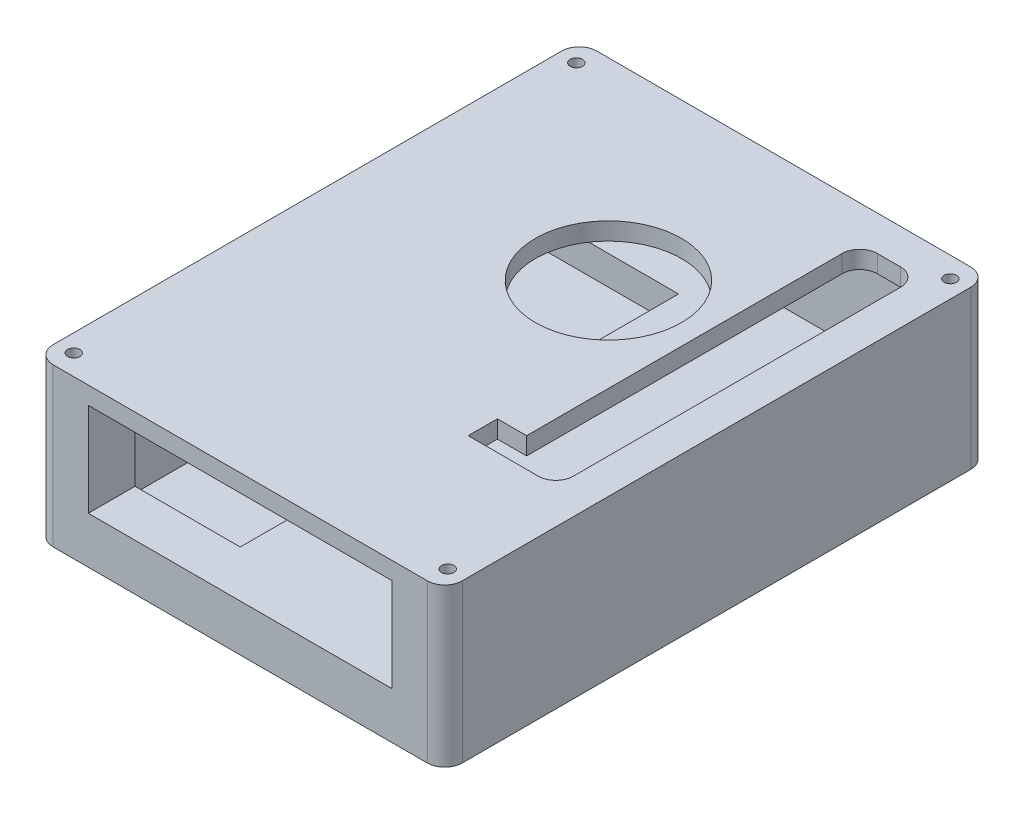
SolidWorks part; units mm, degrees
ref_plane "前视基准面" through (0, 0, 0) normal (0, 0, 1) x (1, 0, 0)
ref_plane "上视基准面" through (0, 0, 0) normal (0, 1, 0) x (1, 0, 0)
ref_plane "右视基准面" through (0, 0, 0) normal (1, 0, 0) x (0, 0, -1)
sketch "草图1" plane through (0, 0, 0) normal (0, 1, 0) x (1, 0, 0)
  line L1 (-32, -46.5) -> (32, -46.5)
  line L2 (-35, -43.5) -> (-35, 43.5)
  line L3 (-32, 46.5) -> (32, 46.5)
  line L4 (35, -43.5) -> (35, 43.5)
  line L5 (-35, -46.5) -> (35, 46.5) construction
  line L6 (-35, 46.5) -> (35, -46.5) construction
  arc A0 (-32, -46.5) -> (-35, -43.5) centre (-32, -43.5) cw
  arc A1 (32, -46.5) -> (35, -43.5) centre (32, -43.5) ccw
  arc A2 (32, 46.5) -> (35, 43.5) centre (32, 43.5) cw
  arc A3 (-35, 43.5) -> (-32, 46.5) centre (-32, 43.5) cw
  point P0 (0, 0)
  dimension "D3" = 3
  dimension "D1" = 93
  dimension "D2" = 70
extrude "凸台-拉伸1" add sketch "草图1" along normal blind 27
sketch "草图2" plane through (-35, 0, 0) normal (-1, 0, 0) x (0, 0, 1)
  line L0 (-43.5, 0) -> (43.5, 0) construction
  line L1 (-36.5, 17) -> (18.5, 17)
  line L2 (-36.5, 17) -> (-36.5, 3)
  line L3 (-36.5, 3) -> (18.5, 3)
  line L4 (18.5, 17) -> (18.5, 3)
  line L5 (-36.5, 17) -> (18.5, 3) construction
  line L6 (-36.5, 3) -> (18.5, 17) construction
  line L7 (-46.5, 27) -> (-46.5, 0) construction
  point P0 (-9, 10)
  point P7 (-5.2874, 10)
  dimension "D1" = 55
  dimension "D2" = 14
  dimension "D3" = 3
  dimension "D4" = 10
extrude "切除-拉伸1" cut sketch "草图2" against normal blind 27
sketch "草图3" plane through (0, 0, 46.5) normal (0, 0, 1) x (1, 0, 0)
  line L0 (0, 0) -> (0, 16) construction
  line L1 (-26, 24) -> (26, 24)
  line L2 (-26, 24) -> (-26, 8)
  line L3 (-26, 8) -> (26, 8)
  line L4 (26, 24) -> (26, 8)
  line L5 (-26, 24) -> (26, 8) construction
  line L6 (-26, 8) -> (26, 24) construction
  line L7 (-32, 0) -> (32, 0) construction
  point P0 (0, 16)
  dimension "D1" = 52
  dimension "D2" = 16
  dimension "D3" = 8
extrude "切除-拉伸2" cut sketch "草图3" against normal blind 90
sketch "草图4" plane through (0, 27, 0) normal (0, 1, 0) x (1, 0, 0)
  line L0 (32, 46.5) -> (-32, 46.5) construction
  line L1 (26, 40.5) -> (22, 40.5)
  line L2 (29, 37.5) -> (29, -18.5)
  line L3 (26, -21.5) -> (19, -21.5)
  line L4 (19, 37.5) -> (19, -16.5)
  line L5 (35, -43.5) -> (35, 43.5) construction
  line L7 (19, -21.5) -> (14, -21.5)
  line L9 (19, -16.5) -> (14, -16.5)
  line L10 (14, -21.5) -> (14, -16.5)
  arc A0 (29, -18.5) -> (26, -21.5) centre (26, -18.5) cw
  arc A1 (22, 40.5) -> (19, 37.5) centre (22, 37.5) ccw
  arc A2 (26, 40.5) -> (29, 37.5) centre (26, 37.5) cw
  circle A3 centre (3, 13.5) radius 12.5
  point P10 (29, -21.5)
  point P13 (19, 40.5)
  point P16 (29, 40.5)
  dimension "D5" = 3
  dimension "D8" = 25
  dimension "D1" = 10
  dimension "D2" = 62
  dimension "D3" = 6
  dimension "D4" = 6
  dimension "D6" = 5
  dimension "D7" = 5
  dimension "D9" = 32
  dimension "D10" = 33
extrude "切除-拉伸3" cut sketch "草图4" against normal up to surface (19 mm away)
sketch "草图5" plane through (0, 0, 18.5) normal (0, 0, -1) x (-1, 0, 0)
  line L0 (26, 17) -> (30, 17)
  line L1 (26, 17) -> (35, 17) construction
  line L2 (30, 17) -> (30, 3)
  line L3 (8, 3) -> (35, 3) construction
  line L4 (30, 3) -> (8, 3)
  line L5 (8, 3) -> (8, 8)
  line L6 (8, 8) -> (26, 8)
  line L7 (26, 8) -> (26, 17)
  line L8 (35, 3) -> (35, 17) construction
  dimension "D1" = 5
extrude "切除-拉伸4" cut sketch "草图5" against normal blind 20
sketch "草图6" plane through (0, 27, 0) normal (0, 1, 0) x (1, 0, 0)
  line L0 (32, 43) -> (-32, 43) construction
  line L1 (-32, 43) -> (-32, -43) construction
  line L2 (-32, -43) -> (32, -43) construction
  line L3 (32, -43) -> (32, 43) construction
  line L4 (32, 46.5) -> (-32, 46.5) construction
  line L5 (-32, -46.5) -> (32, -46.5) construction
  line L6 (35, -43.5) -> (35, 43.5) construction
  line L7 (-35, 43.5) -> (-35, -43.5) construction
  circle A0 centre (-32, 43) radius 1.05
  circle A1 centre (-32, -43) radius 1.05
  circle A2 centre (32, -43) radius 1.05
  circle A3 centre (32, 43) radius 1.05
  dimension "D1" = 2.1
  dimension "D2" = 2.1
  dimension "D3" = 2.1
  dimension "D4" = 2.1
  dimension "D5" = 3.5
  dimension "D6" = 3.5
  dimension "D7" = 3
  dimension "D8" = 3
extrude "切除-拉伸5" cut sketch "草图6" against normal through all
